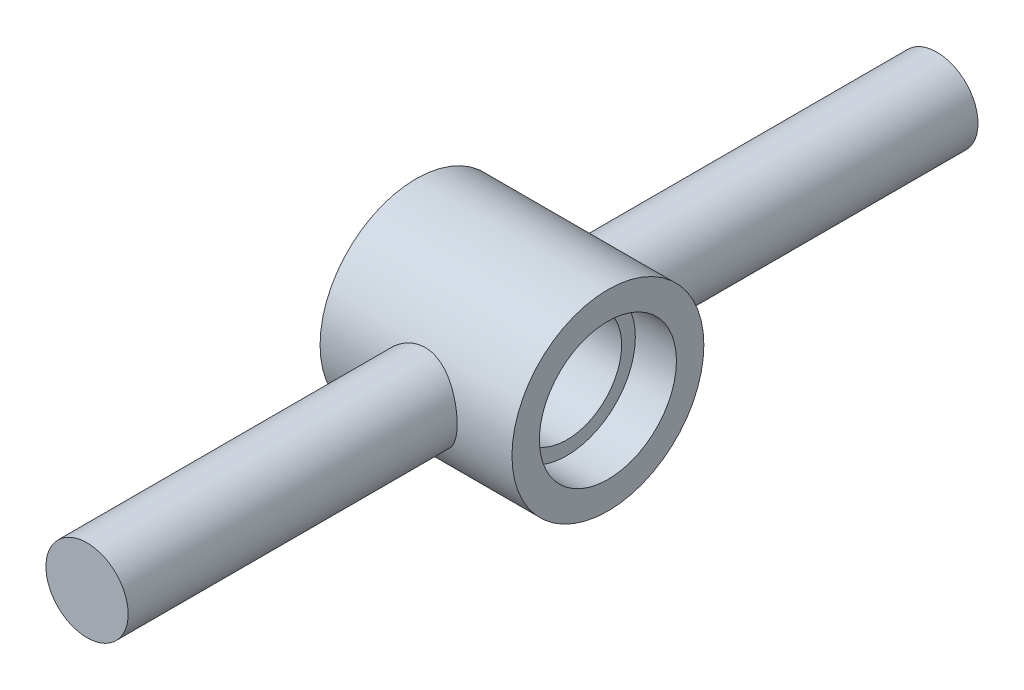
SolidWorks part; units mm, degrees
material "1100-O 棒材(SS)"
ref_plane "前视" through (0, 0, 0) normal (0, 0, 1) x (1, 0, 0)
ref_plane "上视" through (0, 0, 0) normal (0, 1, 0) x (1, 0, 0)
ref_plane "右视" through (0, 0, 0) normal (1, 0, 0) x (0, 0, -1)
sketch "草图1" plane through (0, 0, 0) normal (0, 0, 1) x (1, 0, 0)
  line L0 (-7, 0) -> (7, 0)
  line L2 (7, 0) -> (7, 7)
  line L3 (7, 7) -> (-7, 7)
  line L4 (-7, 0) -> (-7, 7)
  point P0 (0, 0)
  dimension "D1" = 14
  dimension "D2" = 7
  dimension "D3" = 7
revolve "旋转1" add sketch "草图1" angle 360 about L0
sketch "草图2" plane through (0, 0, 0) normal (1, 0, 0) x (0, 0, -1)
  line L0 (-31, 0) -> (31, 0)
  line L1 (31, 0) -> (31, 3)
  line L2 (31, 3) -> (-31, 3)
  line L3 (0, 0) -> (0, 6.1622) construction
  line L4 (-31, 0) -> (-31, 3)
  point P9 (0, 3)
  dimension "D1" = 62
  dimension "D2" = 3
revolve "旋转3" add sketch "草图2" angle 360 about L0
sketch "草图3" plane through (7, 0, 0) normal (1, 0, 0) x (0, 0, -1)
  circle A0 centre (0, 0) radius 4
  dimension "D1" = 8
extrude "切除-拉伸1" cut sketch "草图3" against normal through all
sketch "草图5" plane through (7, 0, 0) normal (1, 0, 0) x (0, 0, -1)
  circle A0 centre (0, 0) radius 5
  dimension "D1" = 10
extrude "切除-拉伸2" cut sketch "草图5" against normal blind 3
mirror "镜向1" about plane through (0, 0, 0) normal (1, 0, 0) of "切除-拉伸2"
